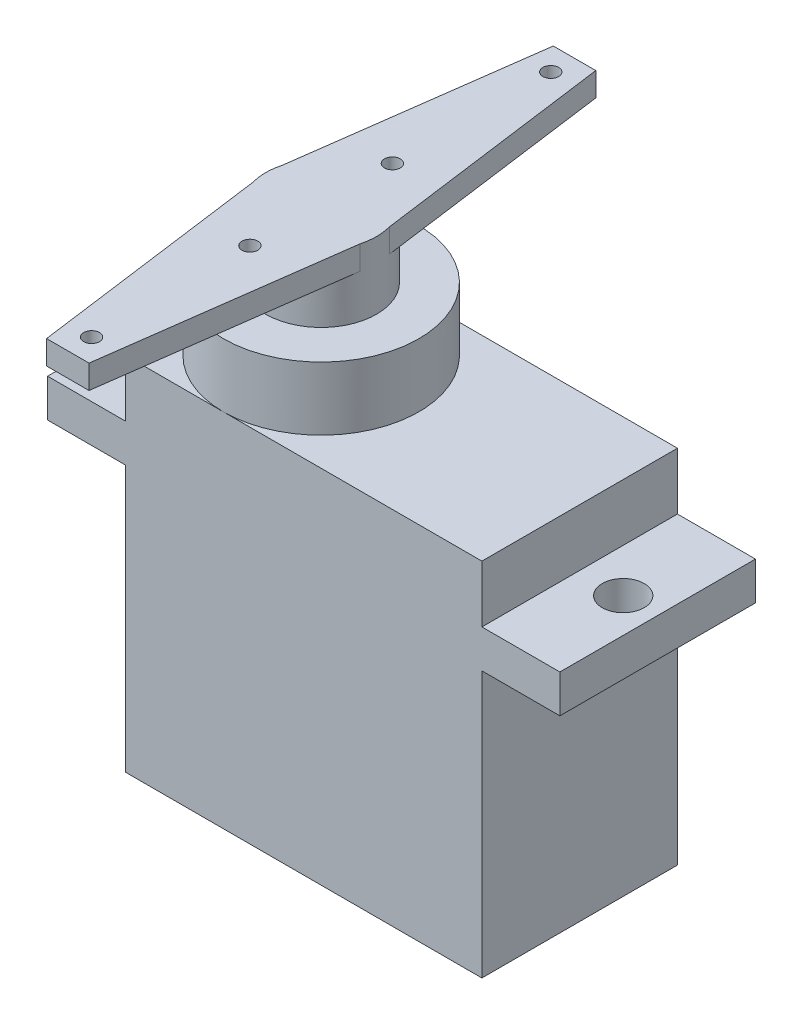
SolidWorks part; units mm, degrees
ref_plane "前视基准面" through (0, 0, 0) normal (0, 0, 1) x (1, 0, 0)
ref_plane "上视基准面" through (0, 0, 0) normal (0, 1, 0) x (1, 0, 0)
ref_plane "右视基准面" through (0, 0, 0) normal (1, 0, 0) x (0, 0, -1)
other "Configuration Table"
sketch "草图1" plane through (0, 0, 0) normal (0, 1, 0) x (1, 0, 0)
  line L1 (-11.25, 6.175) -> (11.25, 6.175)
  line L2 (-11.25, 6.175) -> (-11.25, -6.175)
  line L3 (-11.25, -6.175) -> (11.25, -6.175)
  line L4 (11.25, 6.175) -> (11.25, -6.175)
  line L5 (-11.25, 6.175) -> (11.25, -6.175) construction
  line L6 (-11.25, -6.175) -> (11.25, 6.175) construction
  point P0 (0, 0)
  dimension "D1" = 22.5
  dimension "D2" = 12.35
extrude "凸台-拉伸1" add sketch "草图1" along normal blind 22.8
sketch "草图2" plane through (0, 22.8, 0) normal (0, 1, 0) x (1, 0, 0)
  line L0 (11.25, 6.175) -> (-11.25, 6.175) construction
  line L1 (-16.175, -6.175) -> (16.175, -6.175)
  line L2 (-16.175, -6.175) -> (-16.175, 6.175)
  line L3 (-16.175, 6.175) -> (16.175, 6.175)
  line L4 (16.175, -6.175) -> (16.175, 6.175)
  line L5 (-16.175, -6.175) -> (16.175, 6.175) construction
  line L6 (-16.175, 6.175) -> (16.175, -6.175) construction
  line L7 (-23.1083, 0) -> (25.5685, 0) construction
  line L8 (0, 8.1055) -> (0, -8.413) construction
  circle A0 centre (-14, 0) radius 1.325
  circle A1 centre (14, 0) radius 1.325
  point P0 (0, 0)
  dimension "D2" = 2.65
  dimension "D1" = 32.35
  dimension "D3" = 28
extrude "凸台-拉伸2" add sketch "草图2" against normal blind 2.4 from offset 3.6 offset against normal yes
sketch "草图3" plane through (0, 22.8, 0) normal (0, 1, 0) x (1, 0, 0)
  line L0 (-19.9522, 0) -> (20.7645, 0) construction
  line L1 (-11.25, -6.175) -> (-11.25, 6.175) construction
  line L2 (11.25, 6.175) -> (-11.25, 6.175) construction
  circle A0 centre (-5.075, 0) radius 6.175
extrude "凸台-拉伸3" add sketch "草图3" along normal blind 4
sketch "草图4" plane through (0, 26.8, 0) normal (0, 1, 0) x (1, 0, 0)
  circle A0 centre (-5.075, 0) radius 3.5
  dimension "D1" = 7
extrude "凸台-拉伸4" add sketch "草图4" along normal blind 4.25 separate body
sketch "草图5" plane through (0, 31.05, 0) normal (0, 1, 0) x (1, 0, 0)
  line L0 (-5.075, 0) -> (-5.075, 16.5569) construction
  line L1 (-5.075, 0) -> (-17.2179, 0) construction
  line L2 (-5.075, 0) -> (0, 0) construction
  line L3 (-8.575, 0) -> (-6.4165, 16)
  line L4 (-6.4165, 16) -> (-3.7335, 16)
  line L5 (-1.575, 0) -> (-3.7335, 16)
  line L6 (-1.575, 0) -> (-3.7335, -16)
  line L7 (-8.575, 0) -> (-6.4165, -16)
  line L8 (-6.4165, -16) -> (-3.7335, -16)
  circle A0 centre (-5.075, 0) radius 3.5 construction
  circle A1 centre (-5.075, 14.5) radius 0.5
  circle A2 centre (-5.075, 4.5) radius 0.5
  circle A3 centre (-5.075, -4.5) radius 0.5
  circle A4 centre (-5.075, -14.5) radius 0.5
  dimension "D3" = 1
  dimension "D1" = 90
  dimension "D2" = 16
  dimension "D4" = 4.5
  dimension "D5" = 14.5
extrude "凸台-拉伸5" add sketch "草图5" against normal blind 1.5
